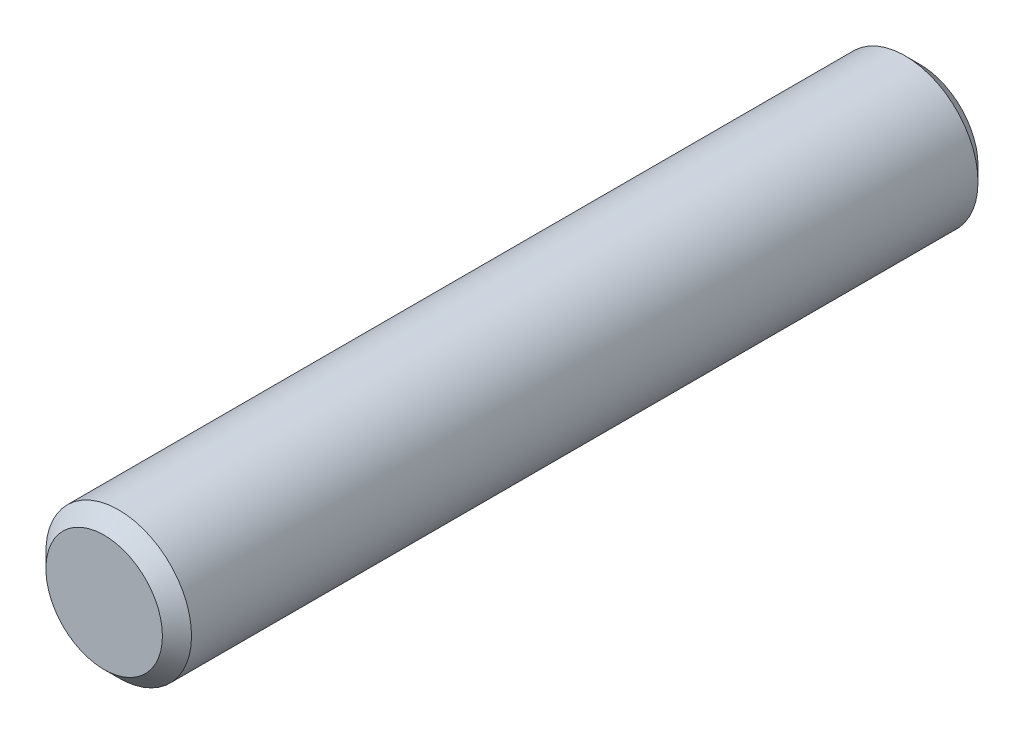
SolidWorks part; units mm, degrees
ref_plane "Front Plane" through (0, 0, 0) normal (0, 0, 1) x (1, 0, 0)
ref_plane "Top Plane" through (0, 0, 0) normal (0, 1, 0) x (1, 0, 0)
ref_plane "Right Plane" through (0, 0, 0) normal (1, 0, 0) x (0, 0, -1)
sketch "Sketch1" plane through (0, 0, 0) normal (0, 0, 1) x (1, 0, 0)
  circle A0 centre (0, 0) radius 2.5
  dimension "D1" = 5
extrude "Boss-Extrude1" add sketch "Sketch1" against normal blind 28
chamfer "Chamfer1" distance 0.5 angle 45 2 edges at (2.5, 0, -28) (2.5, 0, 0)
